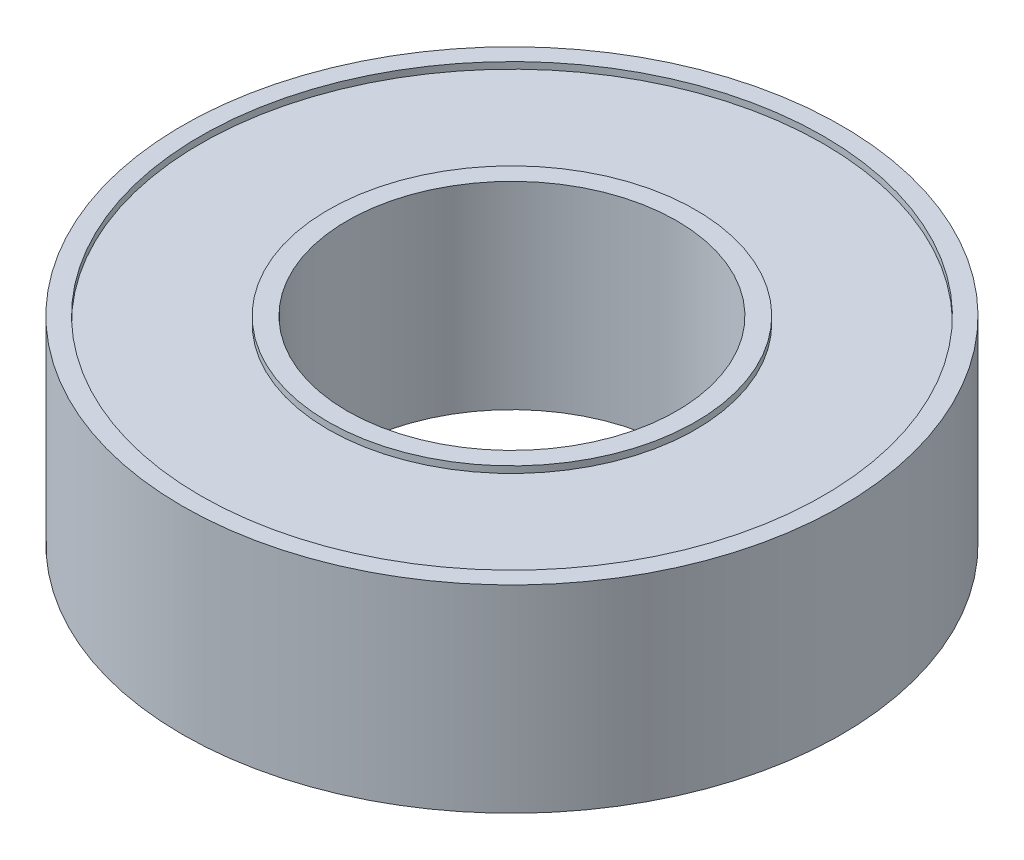
SolidWorks part; units mm, degrees
ref_plane "Front Plane" through (0, 0, 0) normal (0, 0, 1) x (1, 0, 0)
ref_plane "Top Plane" through (0, 0, 0) normal (0, 1, 0) x (1, 0, 0)
ref_plane "Right Plane" through (0, 0, 0) normal (1, 0, 0) x (0, 0, -1)
sketch "Sketch1" plane through (0, 0, 0) normal (0, 1, 0) x (1, 0, 0)
  circle A0 centre (0, 0) radius 5
  circle A1 centre (0, 0) radius 2.5
  dimension "D1" = 10
  dimension "D2" = 5
extrude "Boss-Extrude1" add sketch "Sketch1" along normal blind 3
sketch "Sketch2" plane through (0, 0, 0) normal (0, -1, 0) x (1, 0, 0)
  circle A0 centre (0, 0) radius 4.7252
  circle A1 centre (0, 0) radius 2.7873
extrude "Cut-Extrude1" cut sketch "Sketch2" against normal blind 0.1
sketch "Sketch3" plane through (0, 3, 0) normal (0, 1, 0) x (1, 0, 0)
  circle A0 centre (0, 0) radius 2.7873
  circle A1 centre (0, 0) radius 4.7252
extrude "Cut-Extrude2" cut sketch "Sketch3" against normal blind 0.1
